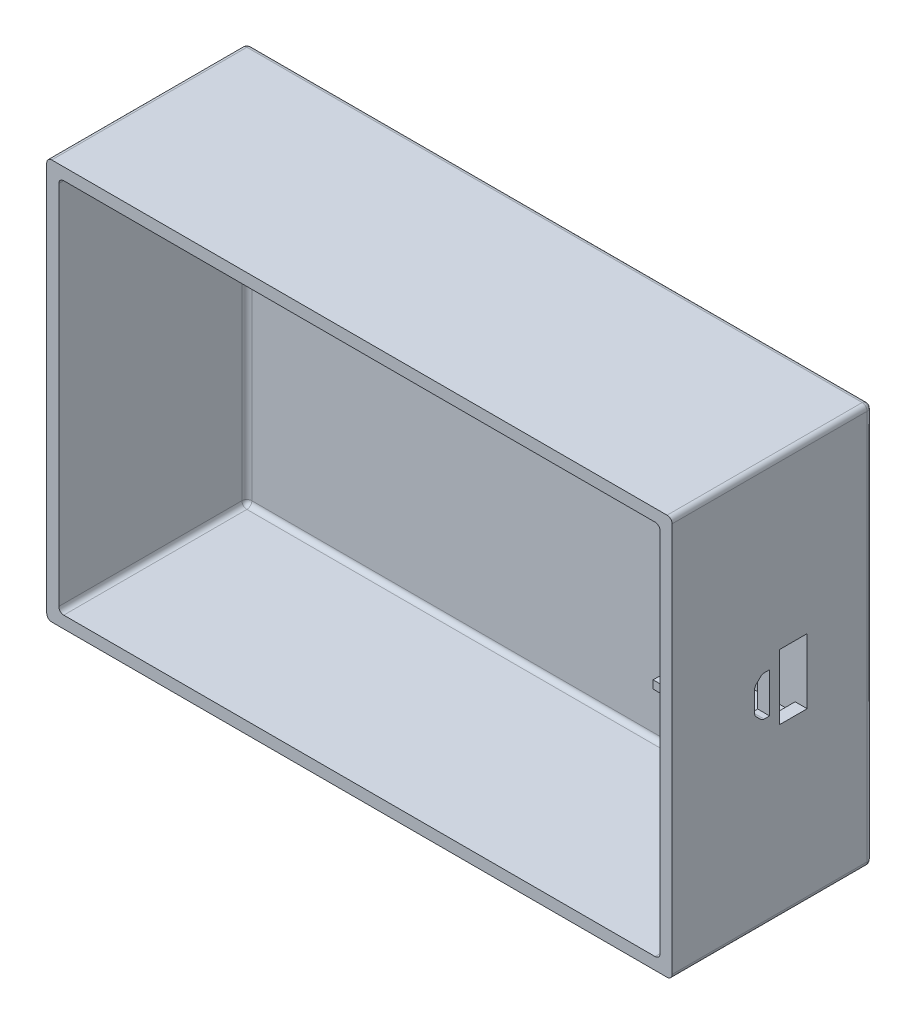
SolidWorks part; units mm, degrees
material "Резина"
ref_plane "Спереди" through (0, 0, 0) normal (0, 0, 1) x (1, 0, 0)
ref_plane "Сверху" through (0, 0, 0) normal (0, 1, 0) x (1, 0, 0)
ref_plane "Справа" through (0, 0, 0) normal (1, 0, 0) x (0, 0, -1)
sketch "Эскиз1" plane through (0, 0, 0) normal (0, 0, 1) x (1, 0, 0)
  line L1 (-62.5, 40) -> (62.5, 40)
  line L2 (-62.5, 40) -> (-62.5, -40)
  line L3 (-62.5, -40) -> (62.5, -40)
  line L4 (62.5, 40) -> (62.5, -40)
  line L5 (-62.5, 40) -> (62.5, -40) construction
  line L6 (-62.5, -40) -> (62.5, 40) construction
  point P0 (0, 0)
  dimension "D1" = 125
  dimension "D2" = 80
extrude "Бобышка-Вытянуть1" add sketch "Эскиз1" along normal blind 40
sketch "Эскиз2" plane through (0, 0, 40) normal (0, 0, 1) x (1, 0, 0)
  line L0 (62.5, 40) -> (-62.5, 40) construction
  line L1 (-60.1, 37.6) -> (60.1, 37.6)
  line L2 (-60.1, 37.6) -> (-60.1, -37.6)
  line L3 (-60.1, -37.6) -> (60.1, -37.6)
  line L4 (60.1, 37.6) -> (60.1, -37.6)
  line L5 (-60.1, 37.6) -> (60.1, -37.6) construction
  line L6 (-60.1, -37.6) -> (60.1, 37.6) construction
  line L7 (62.5, -40) -> (62.5, 40) construction
  point P0 (0, 0)
  dimension "D1" = 2.4
  dimension "D2" = 2.4
extrude "Вырез-Вытянуть1" cut sketch "Эскиз2" against normal blind 37.6
fillet "Скругление1" radius 1 8 edges at (62.5, -40, 20) (62.5, 40, 20) (62.5, 0, 0) (0, 40, 0) (-62.5, 40, 20) (-62.5, -40, 20) (0, -40, 0) (-62.5, 0, 0)
fillet "Скругление2" radius 1 8 edges at (60.1, 37.6, 21.2) (60.1, 0, 2.4) (60.1, -37.6, 21.2) (0, 37.6, 2.4) (-60.1, 37.6, 21.2) (0, -37.6, 2.4) (-60.1, -37.6, 21.2) (-60.1, 0, 2.4)
sketch "Эскиз3" plane through (0, 0, 0) normal (0, 0, -1) x (-1, 0, 0)
  line L0 (-61.5, 5) -> (59.5, 5) construction
  line L4 (-61.5, 39) -> (-61.5, -39) construction
  text T0 "Для\r\nЗСУ" font "Times New Roman" height 20
  dimension "D1" = 5
extrude "Вырез-Вытянуть2" cut sketch "Эскиз3" against normal blind 0.5
sketch "Эскиз4" plane through (62.5, 0, 0) normal (1, 0, 0) x (0, 0, -1)
  line L0 (0, 0) -> (-20.5, 0) construction
  line L1 (-20.5, -4) -> (-20.5, 4)
  line L2 (-20.5, 4) -> (-21.5858, 4)
  line L3 (-23.5, 2.0858) -> (-23.5, -2.0858)
  line L4 (-15.75, 0) -> (-20.5, 0) construction
  line L5 (-13, 6.5) -> (-18.5, 6.5)
  line L6 (-13, 6.5) -> (-13, -6.5)
  line L7 (-13, -6.5) -> (-18.5, -6.5)
  line L8 (-18.5, 6.5) -> (-18.5, -6.5)
  line L9 (-13, 6.5) -> (-18.5, -6.5) construction
  line L10 (-13, -6.5) -> (-18.5, 6.5) construction
  line L11 (-22.2929, 3.7071) -> (-23.2071, 2.7929)
  line L12 (-22.2929, -3.7071) -> (-23.2071, -2.7929)
  line L13 (-20.5, -4) -> (-21.5858, -4)
  arc A0 (-22.2929, -3.7071) -> (-21.5858, -4) centre (-21.5858, -3) ccw
  arc A1 (-23.2071, -2.7929) -> (-23.5, -2.0858) centre (-22.5, -2.0858) cw
  arc A2 (-23.2071, 2.7929) -> (-23.5, 2.0858) centre (-22.5, 2.0858) ccw
  arc A3 (-22.2929, 3.7071) -> (-21.5858, 4) centre (-21.5858, 3) cw
  point P5 (-15.75, 0)
  point P15 (-23.5, 0)
  point P18 (-22, -4)
  point P21 (-23.5, -2.5)
  point P24 (-23.5, 2.5)
  point P27 (-22, 4)
  dimension "D9" = 1
  dimension "D1" = 13
  dimension "D2" = 5.5
  dimension "D3" = 13
  dimension "D4" = 2
  dimension "D5" = 3
  dimension "D6" = 8
  dimension "D7" = 1.5
  dimension "D8" = 1.5
extrude "Вырез-Вытянуть3" cut sketch "Эскиз4" against normal blind 5
sketch "Эскиз5" plane through (60.1, 0, 0) normal (-1, 0, 0) x (0, 0, 1)
  line L0 (11.4, 0) -> (29.8169, 0) construction
  line L1 (11.4, 0) -> (11.4, -8.5)
  line L2 (11.4, -8.5) -> (13, -8.5)
  line L3 (13, -8.5) -> (13, 8.5)
  line L4 (11.4, 0) -> (11.4, 8.5)
  line L5 (11.4, 8.5) -> (13, 8.5)
  line L13 (0, -39) -> (0, 39) construction
  line L15 (11.4, -8.5) -> (21.4, -8.5)
  line L16 (11.4, -8.5) -> (11.4, -10.1)
  line L17 (11.4, -10.1) -> (21.4, -10.1)
  line L18 (21.4, -8.5) -> (21.4, -10.1)
  line L19 (11.4, -8.5) -> (21.4, -10.1) construction
  line L20 (11.4, -10.1) -> (21.4, -8.5) construction
  point P8 (16.4, -9.3)
  line M18 (18.5, 6.5) -> (18.5, -6.5)
  dimension "D1" = 1.6
  dimension "D2" = 17
  dimension "D3" = 8.5
  dimension "D4" = 13
  dimension "D5" = 17
  dimension "D6" = 1.6
  dimension "D7" = 10
  dimension "D8" = 11.4
extrude "Бобышка-Вытянуть2" add sketch "Эскиз5" along normal blind 20 contours L0 L1 L2 L3 M18 | L18 L15 L2 L16 L17
sketch "Эскиз6" plane through (0, 0, 13) normal (0, 0, 1) x (1, 0, 0)
  line L0 (40.1, 0) -> (43.5026, 0) construction
  line L1 (40.1, -8.5) -> (40.1, 8.5) construction
  line L2 (40.1, 8.5) -> (60.1, 8.5) construction
  line L3 (43.6526, -1.5) -> (43.3526, -1.5)
  line L4 (43.9026, -1.25) -> (43.9026, 1.25)
  line L5 (43.6526, 1.5) -> (43.3526, 1.5)
  line L6 (43.1026, -1.25) -> (43.1026, 1.25)
  line L7 (43.9026, -1.5) -> (43.1026, 1.5) construction
  line L8 (43.9026, 1.5) -> (43.1026, -1.5) construction
  line L9 (45.9832, 6.5) -> (43.9832, 6.5)
  line L10 (46.2332, 6.75) -> (46.2332, 7.05)
  line L11 (45.9832, 7.3) -> (43.9832, 7.3)
  line L12 (43.7332, 6.75) -> (43.7332, 7.05)
  line L13 (46.2332, 6.5) -> (43.7332, 7.3) construction
  line L14 (46.2332, 7.3) -> (43.7332, 6.5) construction
  arc A0 (43.9026, 1.25) -> (43.6526, 1.5) centre (43.6526, 1.25) ccw
  arc A1 (43.1026, 1.25) -> (43.3526, 1.5) centre (43.3526, 1.25) cw
  arc A2 (43.3526, -1.5) -> (43.1026, -1.25) centre (43.3526, -1.25) cw
  arc A3 (43.9026, -1.25) -> (43.6526, -1.5) centre (43.6526, -1.25) cw
  arc A4 (43.7332, 7.05) -> (43.9832, 7.3) centre (43.9832, 7.05) cw
  arc A5 (43.9832, 6.5) -> (43.7332, 6.75) centre (43.9832, 6.75) cw
  arc A6 (46.2332, 7.05) -> (45.9832, 7.3) centre (45.9832, 7.05) ccw
  arc A7 (46.2332, 6.75) -> (45.9832, 6.5) centre (45.9832, 6.75) cw
  point P8 (44.9832, 6.9)
  point P15 (44.9832, 7.3)
  point P16 (43.5026, 0.5)
  point P17 (45.007, 7.2)
  point P18 (44.9832, 7)
  dimension "D7" = 0.25
  dimension "D8" = 0.25
  dimension "D1" = 0.8
  dimension "D2" = 3
  dimension "D3" = 8.5
  dimension "D4" = 0.8
  dimension "D5" = 2.5
  dimension "D6" = 1.2
extrude "Бобышка-Вытянуть3" add sketch "Эскиз6" along normal blind 8
